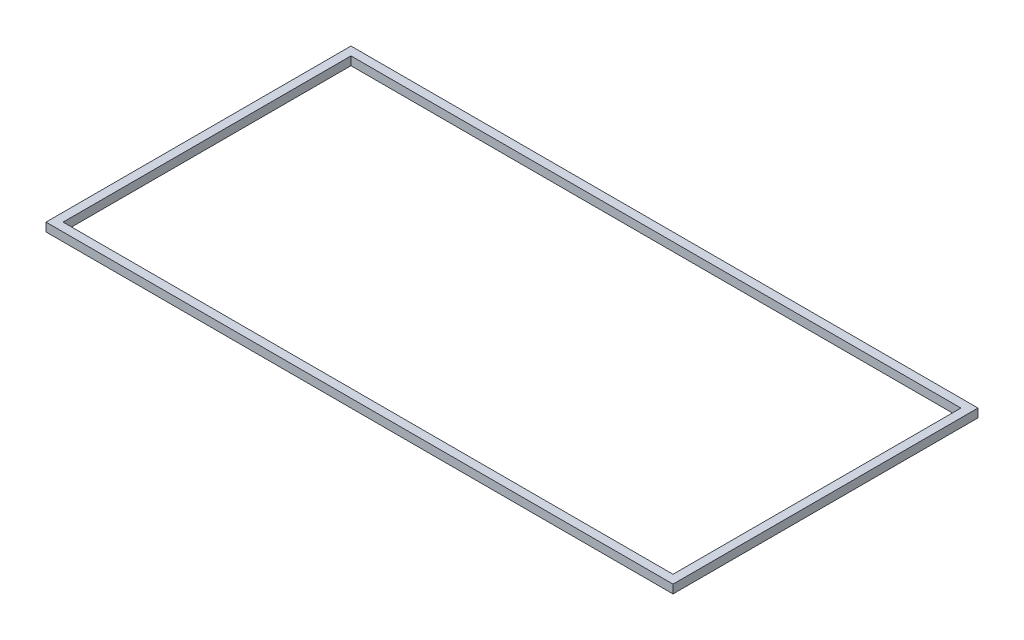
SolidWorks part; units mm, degrees
ref_plane "Front Plane" through (0, 0, 0) normal (0, 0, 1) x (1, 0, 0)
ref_plane "Top Plane" through (0, 0, 0) normal (0, 1, 0) x (1, 0, 0)
ref_plane "Right Plane" through (0, 0, 0) normal (1, 0, 0) x (0, 0, -1)
sketch "Sketch1" plane through (0, 0, 0) normal (0, 1, 0) x (1, 0, 0)
  line L0 (-14, -14) -> (-1014, -14)
  line L1 (0, 0) -> (-1028, 0)
  line L2 (0, 0) -> (0, -500)
  line L3 (0, -500) -> (-1028, -500)
  line L4 (-1028, 0) -> (-1028, -500)
  line L5 (-1014, -14) -> (-1014, -486)
  line L6 (-14, -486) -> (-1014, -486)
  line L7 (-14, -14) -> (-14, -486)
  dimension "D1" = 1028
  dimension "D2" = 500
  dimension "D3" = 14
extrude "Boss-Extrude1" add sketch "Sketch1" along normal blind 14 contours L7 L0 L5 L6 | L4 L3 L2 L1
